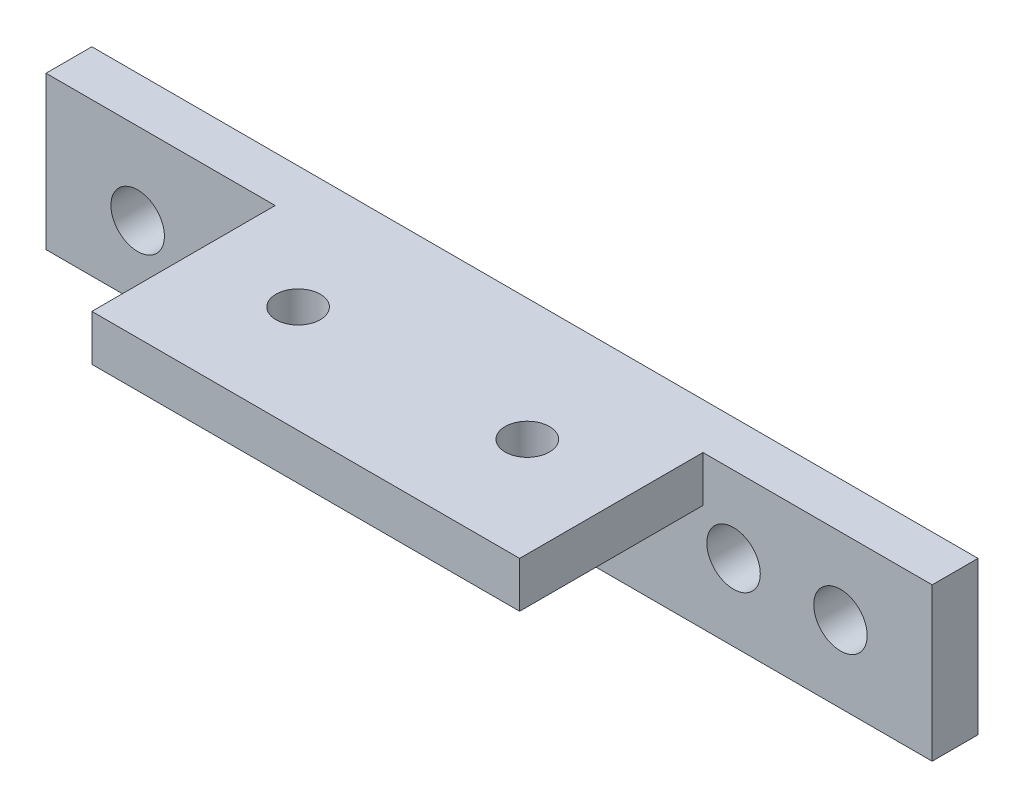
SolidWorks part; units mm, degrees
ref_plane "Front Plane" through (0, 0, 0) normal (0, 0, 1) x (1, 0, 0)
ref_plane "Top Plane" through (0, 0, 0) normal (0, 1, 0) x (1, 0, 0)
ref_plane "Right Plane" through (0, 0, 0) normal (1, 0, 0) x (0, 0, -1)
sketch "Sketch1" plane through (0, 0, 0) normal (0, 1, 0) x (1, 0, 0)
  line L1 (0, 0) -> (28, 0)
  line L2 (0, 0) -> (0, -12)
  line L3 (0, -12) -> (28, -12)
  line L4 (28, 0) -> (28, -12)
  circle A0 centre (6.5, -5) radius 1.45
  circle A1 centre (21.5, -5) radius 1.45
  dimension "D3" = 2.9
  dimension "D4" = 2.9
  dimension "D1" = 28
  dimension "D2" = 12
  dimension "D5" = 15
  dimension "D6" = 6.5
  dimension "D7" = 5
  dimension "D8" = 5
extrude "Boss-Extrude1" add sketch "Sketch1" along normal blind 3
sketch "Sketch2" plane through (0, 3, 0) normal (0, 1, 0) x (1, 0, 0)
  line L0 (0, -12) -> (28, -12) construction
  line L1 (43, 0) -> (-15, 0)
  line L2 (43, 0) -> (43, 3)
  line L3 (43, 3) -> (-15, 3)
  line L4 (-15, 0) -> (-15, 3)
  point P6 (14, -12)
  dimension "D1" = 3
  dimension "D2" = 58
  dimension "D3" = 29
extrude "Boss-Extrude2" add sketch "Sketch2" against normal blind 10
sketch "Sketch3" plane through (0, 0, -3) normal (0, 0, -1) x (-1, 0, 0)
  line L0 (15, -7) -> (15, 3) construction
  line L3 (-43, -7) -> (15, -7) construction
  line L4 (-43, -7) -> (-43, 3) construction
  circle A0 centre (9, -2.3595) radius 1.75
  circle A1 centre (-36.9986, -2) radius 1.75
  circle A2 centre (2, -2) radius 1.75
  circle A3 centre (-30, -2) radius 1.75
  dimension "D1" = 3.5
  dimension "D2" = 3.5
  dimension "D6" = 3.5
  dimension "D7" = 3.5
  dimension "D3" = 6
  dimension "D4" = 46
  dimension "D5" = 5
  dimension "D8" = 32
  dimension "D9" = 13
  dimension "D10" = 5
  dimension "D11" = 5
extrude "Cut-Extrude1" cut sketch "Sketch3" against normal blind 12
equation "\"D2@Sketch2\"=46+6*2"
equation "\"D3@Sketch2\"=\"D2@Sketch2\"/2"
equation "\"D9@Sketch3\"=\"D4@Sketch3\"/2-32/2+6"
